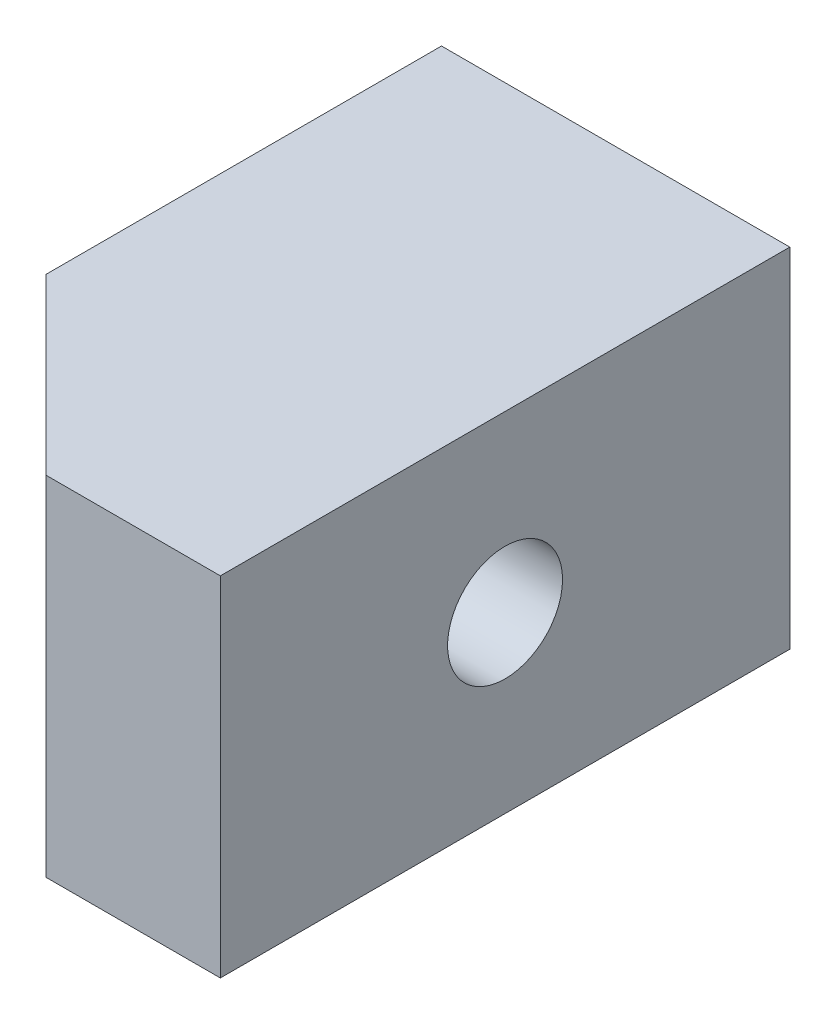
SolidWorks part; units mm, degrees
ref_plane "Front Plane" through (0, 0, 0) normal (0, 0, 1) x (1, 0, 0)
ref_plane "Top Plane" through (0, 0, 0) normal (0, 1, 0) x (1, 0, 0)
ref_plane "Right Plane" through (0, 0, 0) normal (1, 0, 0) x (0, 0, -1)
sketch "Sketch1" plane through (0, 0, 0) normal (0, 1, 0) x (1, 0, 0)
  line L1 (-5, -8.175) -> (5, -8.175)
  line L2 (-5, -8.175) -> (-5, 8.175)
  line L3 (-5, 8.175) -> (5, 8.175)
  line L4 (5, -8.175) -> (5, 8.175)
  line L5 (-5, -8.175) -> (5, 8.175) construction
  line L6 (-5, 8.175) -> (5, -8.175) construction
  point P0 (0, 0)
  dimension "D1" = 10
  dimension "D2" = 16.35
extrude "Boss-Extrude1" add sketch "Sketch1" along normal blind 10
chamfer "Chamfer1" distance 5 angle 45 1 edges at (-5, 5, 8.175)
hole_wizard "M4x0.7 Tapped Hole1" positions "Sketch2" profile "Sketch3" tap size "M4x0.7" standard "ANSI Metric"
sketch "Sketch2" plane through (5, 0, 0) normal (1, 0, 0) x (0, 0, -1)
  point P0 (0, 5)
  point P4 (0, 0)
  dimension "D1" = 5
cosmetic thread "Hole Thread1" parameters "D1"=10.08, "D2"=4
sketch "Sketch3" plane through (5, 5, 0) normal (0, 1, 0) x (0, 0, -1)
  line L0 (0, 0) -> (0, 5.8164)
  line L1 (0, 5.8164) -> (1.65, 4.825)
  line L2 (1.65, 4.825) -> (1.65, 0)
  line L5 (1.65, 0) -> (0, 0)
  line L10 (0, 5.8164) -> (-1.65, 4.825) construction
  line L11 (0, -6.35) -> (0, 107.95) construction
  dimension "Tap Drill Dia." = 3.3
  dimension "Tap Drill Depth" = 4.825
  dimension "Drill Angle" = 118
hole_wizard "M4x0.7 Tapped Hole2" positions "Sketch4" profile "Sketch5" tap size "M4x0.7" standard "ANSI Metric"
sketch "Sketch4" plane through (0, 0, -8.175) normal (0, 0, -1) x (-1, 0, 0)
  point P0 (0, 5)
  point P3 (0, 0)
  dimension "D1" = 5
cosmetic thread "Hole Thread2" parameters "D1"=5.16, "D2"=4
sketch "Sketch5" plane through (0, 5, -8.175) normal (1, 0, 0) x (0, 1, 0)
  line L0 (0, 0) -> (0, 5.8164)
  line L1 (0, 5.8164) -> (1.65, 4.825)
  line L2 (1.65, 4.825) -> (1.65, 0)
  line L5 (1.65, 0) -> (0, 0)
  line L10 (0, 5.8164) -> (-1.65, 4.825) construction
  line L11 (0, -6.35) -> (0, 107.95) construction
  dimension "Tap Drill Dia." = 3.3
  dimension "Tap Drill Depth" = 4.825
  dimension "Drill Angle" = 118
